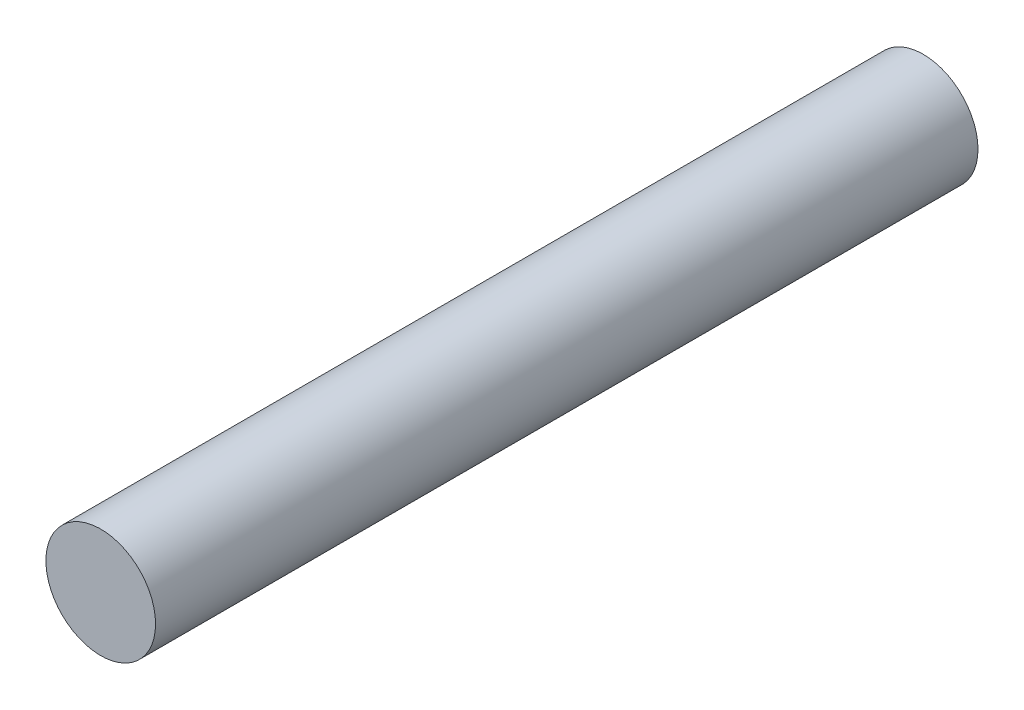
SolidWorks part; units mm, degrees
ref_plane "前视基准面" through (0, 0, 0) normal (0, 0, 1) x (1, 0, 0)
ref_plane "上视基准面" through (0, 0, 0) normal (0, 1, 0) x (1, 0, 0)
ref_plane "右视基准面" through (0, 0, 0) normal (1, 0, 0) x (0, 0, -1)
other "Configuration Table"
sketch "草图1" plane through (0, 0, 0) normal (0, 0, 1) x (1, 0, 0)
  circle A0 centre (0, 0) radius 2
  dimension "D1" = 4
extrude "凸台-拉伸1" add sketch "草图1" along normal blind 30
